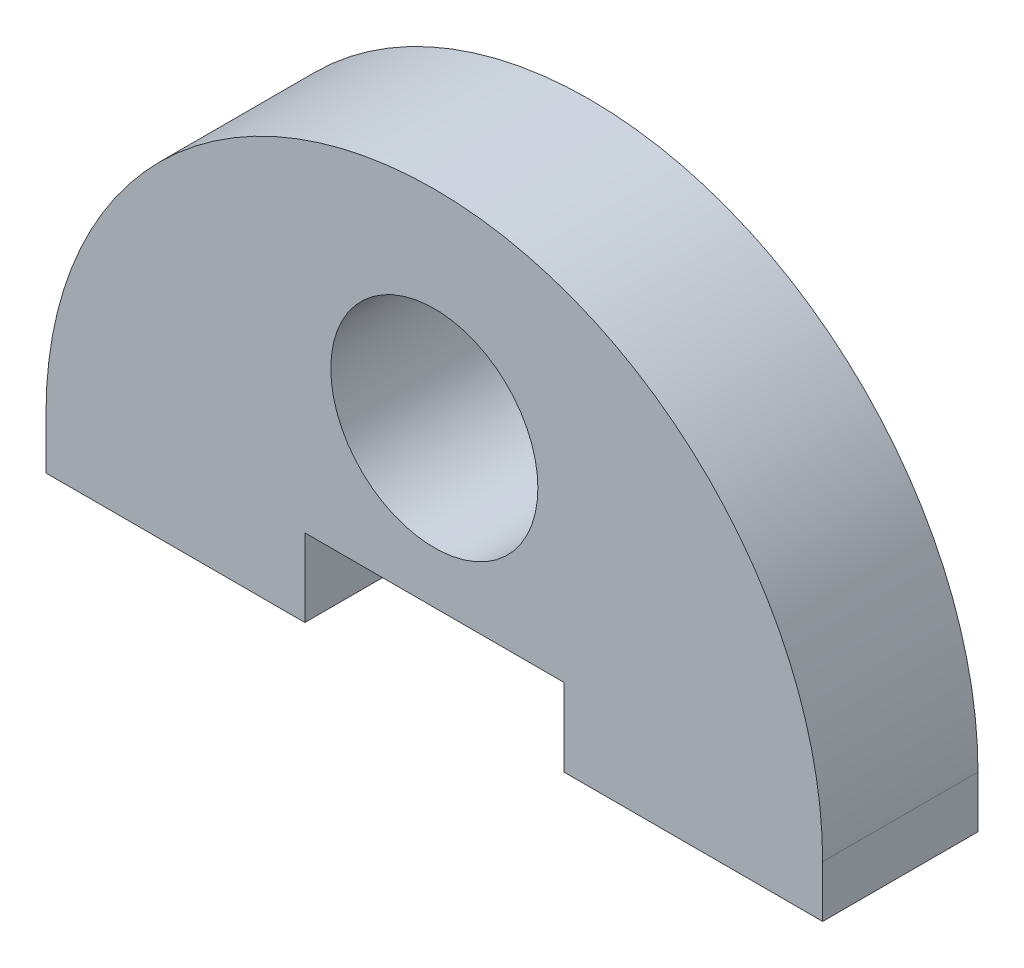
SolidWorks part; units mm, degrees
ref_plane "Front Plane" through (0, 0, 0) normal (0, 0, 1) x (1, 0, 0)
ref_plane "Top Plane" through (0, 0, 0) normal (0, 1, 0) x (1, 0, 0)
ref_plane "Right Plane" through (0, 0, 0) normal (1, 0, 0) x (0, 0, -1)
sketch "Sketch1" plane through (0, 0, 0) normal (0, 0, 1) x (1, 0, 0)
  line L0 (0, 0) -> (10, 0)
  line L1 (10, 0) -> (10, 3)
  line L2 (10, 3) -> (20, 3)
  line L3 (20, 3) -> (20, 0)
  line L4 (20, 0) -> (30, 0)
  line L5 (30, 0) -> (30, 2)
  line L6 (0, 0) -> (0, 2)
  arc A0 (0, 2) -> (30, 2) centre (15, 2) cw
  circle A1 centre (15, 9) radius 4
  dimension "D4" = 2
  dimension "D5" = 8
  dimension "D6" = 6
  dimension "D7" = 15
  dimension "D1" = 3
  dimension "D2" = 10
  dimension "D3" = 30
extrude "Boss-Extrude1" add sketch "Sketch1" along normal blind 6
